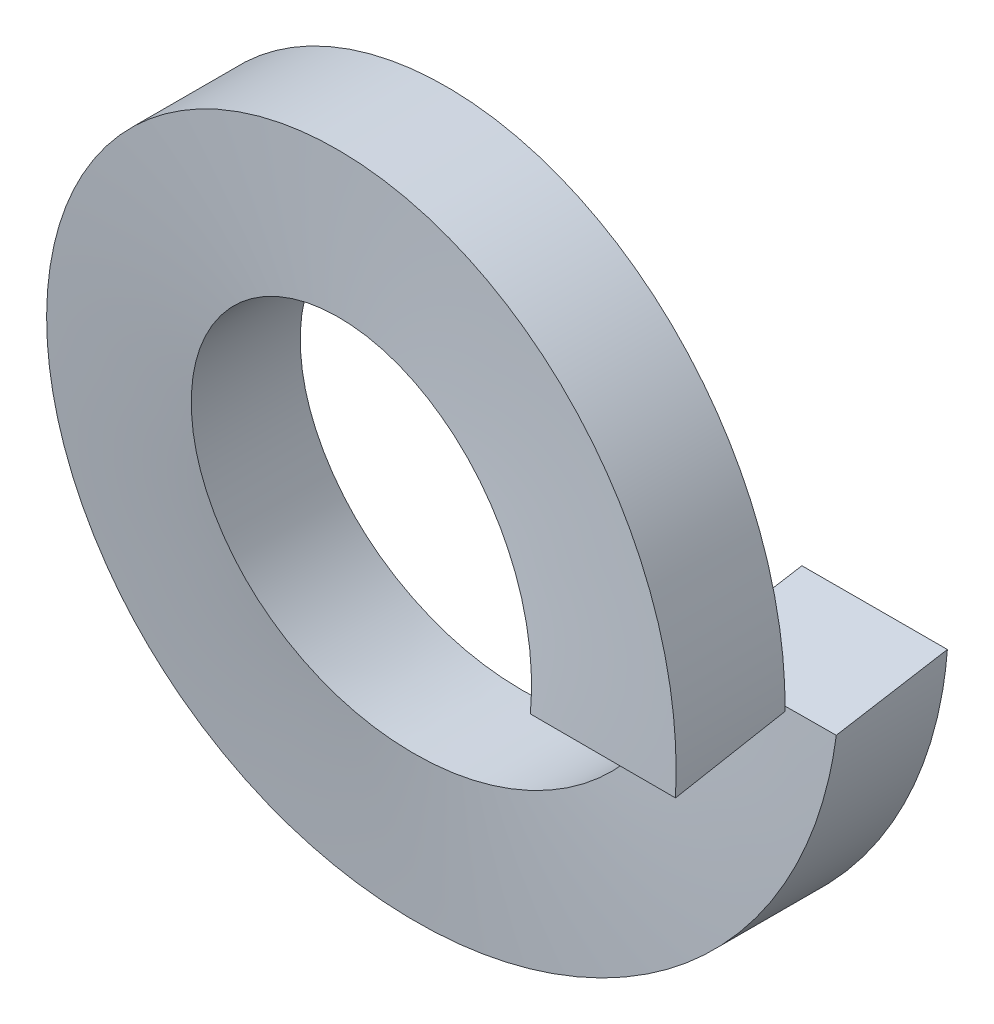
SolidWorks part; units mm, degrees
ref_plane "前视基准面" through (0, 0, 0) normal (0, 0, 1) x (1, 0, 0)
ref_plane "上视基准面" through (0, 0, 0) normal (0, 1, 0) x (1, 0, 0)
ref_plane "右视基准面" through (0, 0, 0) normal (1, 0, 0) x (0, 0, -1)
sketch "草图1" plane through (0, 0, 0) normal (0, 0, 1) x (1, 0, 0)
  line L0 (0, 0) -> (5.765, 0) construction
  line L1 (5.765, 0) -> (9.765, 0) construction
  circle A0 centre (0, 0) radius 5.765
  circle A1 centre (0, 0) radius 9.765
  dimension "d1" = 11.53
  dimension "b" = 4
sketch "草图2" plane through (0, 0, 0) normal (1, 0, 0) x (0, 0, -1)
  line L0 (0, 9.765) -> (0, -9.765) construction
  line L1 (0, 9.765) -> (0, -9.765) construction
  line L2 (1.5, 9.765) -> (-1.5, 9.765)
  line L3 (-3.75, 0) -> (3.75, 0) construction
  line L4 (3.75, 0) -> (0, -0.6612) construction
  point P4 (0, 9.765)
  point P8 (-1.5, 0)
  dimension "S" = 3
  dimension "d2" = 19.53
  dimension "H" = 7.5
  dimension "D3" = 80
  dimension "m" = 1.5
ref_plane "基准面1" through (0, 0, 3.75) normal (0, 0, 1) x (1, 0, 0)
sketch "草图3" plane through (0, 0, 3.75) normal (0, 0, 1) x (1, 0, 0)
  circle A0 centre (0, 0) radius 9.765 construction
  circle A1 centre (0, 0) radius 9.765
curve "螺旋线/涡状线1" pitch 4.5 height 4.5 turns 1
sketch "草图4" plane through (0, 0, 0) normal (0, 1, 0) x (1, 0, 0)
  line L0 (-5.765, 0) -> (5.765, 0) construction
  line L1 (9.765, -3.75) -> (5.765, -3.75)
  line L2 (9.765, -3.75) -> (9.765, -0.75)
  line L3 (9.765, -0.75) -> (5.765, -0.75)
  line L4 (5.765, -3.75) -> (5.765, -0.75)
  line L5 (-5.765, 0) -> (5.765, 0) construction
  spline S0 degree 3 poles (-989.9734, 18.9157) (-156.834, -9.0954) (29.3375, -6.0656) (7.0847, -3.1876) (3.8342, -2.9062) (0, -2.625) (-3.8342, -2.3437) (-7.0847, -2.0625) (-9.2566, -1.7812) (-10.0192, -1.5) (-9.2566, -1.2188) (-7.0847, -0.9375) (-3.8342, -0.6563) (0, -0.375) (3.8342, -0.0938) (7.0847, 0.1876) (29.3374, 3.0656) (-156.8329, 6.0954) (-989.9661, -21.9154) knots -1.733591 -1.733591 -1.733591 -1.733591 0.0625 0.125 0.1875 0.25 0.3125 0.375 0.4375 0.5 0.5625 0.625 0.6875 0.75 0.8125 0.875 0.9375 2.733586 2.733586 2.733586 2.733586 only from (9.765, -3.75) to (9.765, 0.75) construction
  spline S1 degree 3 poles (9.765, -3.75) (9.765, -3.6568) (9.2566, -3.4685) (7.0847, -3.1876) (3.8342, -2.9062) (0, -2.625) (-3.8342, -2.3437) (-7.0847, -2.0625) (-9.2566, -1.7812) (-10.0192, -1.5) (-9.2566, -1.2188) (-7.0847, -0.9375) (-3.8342, -0.6563) (0, -0.375) (3.8342, -0.0938) (7.0847, 0.1876) (9.2566, 0.4685) (9.765, 0.6568) (9.765, 0.75) knots 0 0 0 0 0.0625 0.125 0.1875 0.25 0.3125 0.375 0.4375 0.5 0.5625 0.625 0.6875 0.75 0.8125 0.875 0.9375 1 1 1 1 construction
  dimension "D1" = 3
sweep "扫描1" add profiles "草图4" path "螺旋线/涡状线1"
sketch "草图5" plane through (0, 0, 0) normal (1, 0, 0) x (0, 0, -1)
  line L0 (0, 0) -> (3.75, 0.6612) construction
  line L1 (3.75, 0) -> (0, -0.6612) construction
  line L2 (-7.5, -0.5609) -> (7.5, 2.084)
  line L3 (7.5, 2.084) -> (7.7605, 0.6068)
  line L4 (-7.2395, -2.0381) -> (7.7605, 0.6068)
  line L5 (-7.5, -0.5609) -> (-7.2395, -2.0381)
  line L6 (0, 5.765) -> (0, -5.765) construction
  line L7 (0, 5.765) -> (0, -5.765) construction
  dimension "D1" = 1.5
  dimension "D2" = 15
  dimension "D3" = 15
extrude "切除-拉伸2" cut sketch "草图5" along normal through all
sketch "草图6" [suppressed] plane through (0, 0, 0) normal (0, 0, 1) x (1, 0, 0)
  circle A0 centre (0, 0) radius 8.295 construction
  circle A1 centre (0, 0) radius 4.795 construction
  circle A2 centre (0, 0) radius 8.295
  circle A3 centre (0, 0) radius 4.795
extrude "凸台-拉伸1" [suppressed] add sketch "草图6" along normal up to vertex and the other way up to vertex
sketch "草图7" [suppressed] plane through (0, 0, 0) normal (1, 0, 0) x (0, 0, -1)
  line L0 (0, 0) -> (12.6085, 2.2232) construction
  line L1 (3.125, 0) -> (0, -0.551) construction
  line L2 (12.7171, 1.6077) -> (12.5, 2.8387)
  line L3 (12.5, 2.8387) -> (-12.5, -1.5694)
  line L4 (-12.5, -1.5694) -> (-12.3915, -2.185)
  line L5 (-12.2829, -2.8005) -> (-12.3915, -2.185)
  line L6 (12.7171, 1.6077) -> (-12.2829, -2.8005)
  line L7 (0, 8.295) -> (0, -8.295) construction
  line L8 (0, 8.295) -> (0, -8.295) construction
  dimension "D1" = 1.5
  dimension "D2" = 15
  dimension "D3" = 15
extrude "切除-拉伸3" [suppressed] cut sketch "草图7" along normal through all
